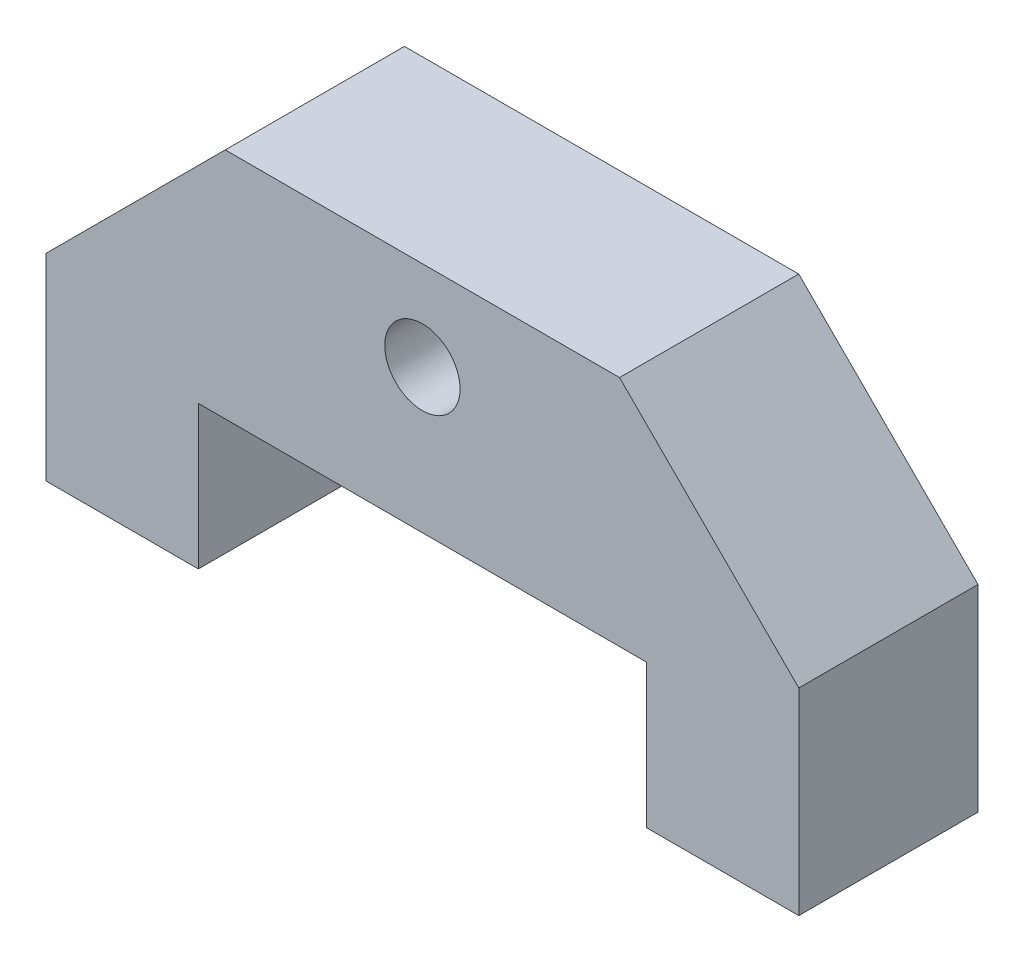
SolidWorks part; units mm, degrees
material "45#"
ref_plane "前视" through (0, 0, 0) normal (0, 0, 1) x (1, 0, 0)
ref_plane "上视" through (0, 0, 0) normal (0, 1, 0) x (1, 0, 0)
ref_plane "右视" through (0, 0, 0) normal (1, 0, 0) x (0, 0, -1)
sketch "草图1" plane through (0, 0, 0) normal (0, 0, 1) x (1, 0, 0)
  line L1 (-21, -10.5) -> (21, -10.5)
  line L2 (-21, -10.5) -> (-21, 10.5)
  line L3 (-21, 10.5) -> (21, 10.5)
  line L4 (21, -10.5) -> (21, 10.5)
  line L5 (-21, -10.5) -> (21, 10.5) construction
  line L6 (-21, 10.5) -> (21, -10.5) construction
  point P0 (0, 0)
  dimension "D1" = 42
  dimension "D2" = 21
extrude "凸台-拉伸1" add sketch "草图1" along normal mid plane 10
sketch "草图2" plane through (0, 0, 5) normal (0, 0, 1) x (1, 0, 0)
  line L0 (0, -10.5) -> (0, 4.4074) construction
  line L1 (-21, -10.5) -> (21, -10.5) construction
  line L3 (-12.5, -2.5) -> (12.5, -2.5)
  line L4 (-12.5, -2.5) -> (-12.5, -10.5)
  line L5 (-12.5, -10.5) -> (12.5, -10.5)
  line L6 (12.5, -2.5) -> (12.5, -10.5)
  line L7 (-12.5, -2.5) -> (12.5, -10.5) construction
  line L8 (-12.5, -10.5) -> (12.5, -2.5) construction
  point P5 (0, -6.5)
  dimension "D1" = 25
  dimension "D2" = 8
extrude "切除-拉伸1" cut sketch "草图2" against normal through all
hole_wizard "M4 螺纹孔1" positions "草图4" profile "草图3" tap size "M4" standard "Gb"
sketch "草图4" plane through (0, -10.5, 0) normal (0, -1, 0) x (-1, 0, 0)
  line L0 (21, 0) -> (0, 0) construction
  line L1 (21, -5) -> (21, 5) construction
  line L2 (0, 0) -> (0, -5) construction
  line L3 (-12.5, -5) -> (12.5, -5) construction
  point P0 (16, 0)
  point P14 (-16, 0)
  dimension "D1" = 32
sketch "草图3" plane through (-16, -10.5, 0) normal (1, 0, 0) x (0, 0, -1)
  line L0 (0, 0) -> (0, 11.0914)
  line L1 (0, 11.0914) -> (1.65, 10.1)
  line L2 (1.65, 10.1) -> (1.65, 0)
  line L5 (1.65, 0) -> (0, 0)
  line L10 (0, 11.0914) -> (-1.65, 10.1) construction
  line L11 (0, -6.35) -> (0, 107.95) construction
  dimension "螺纹孔钻头直径" = 3.3
  dimension "螺纹孔钻头深度" = 10.1
  dimension "导头角度" = 118
cosmetic thread "孔螺蚊线1" parameters "D1"=8, "D2"=4
cosmetic thread "孔螺蚊线2" parameters "D1"=8, "D2"=4
hole_wizard "M5 螺纹孔1" positions "草图6" profile "草图5" tap size "M5" standard "Gb" end condition through all
sketch "草图6" plane through (0, 0, 5) normal (0, 0, 1) x (1, 0, 0)
  line L0 (0, 10.5) -> (0, -2.5) construction
  line L1 (21, 10.5) -> (-21, 10.5) construction
  line L2 (12.5, -2.5) -> (-12.5, -2.5) construction
  line L3 (12.5, -10.5) -> (21, -10.5) construction
  point P0 (0, 5.5)
  dimension "D1" = 16
sketch "草图5" plane through (0, 5.5, 5) normal (1, 0, 0) x (0, -1, 0)
  line L0 (0, 0) -> (0, 10)
  line L1 (0, 10) -> (2.1, 10)
  line L2 (2.1, 10) -> (2.1, 0)
  line L5 (2.1, 0) -> (0, 0)
  line L11 (0, -6.35) -> (0, 107.95) construction
  dimension "通孔螺纹孔钻头直径" = 4.2
  dimension "通孔螺纹孔钻头深度" = 10
cosmetic thread "孔螺蚊线3" parameters "D2"=5
chamfer "倒角1" distance 10 angle 45 2 edges at (21, 10.5, 0) (-21, 10.5, 0)
